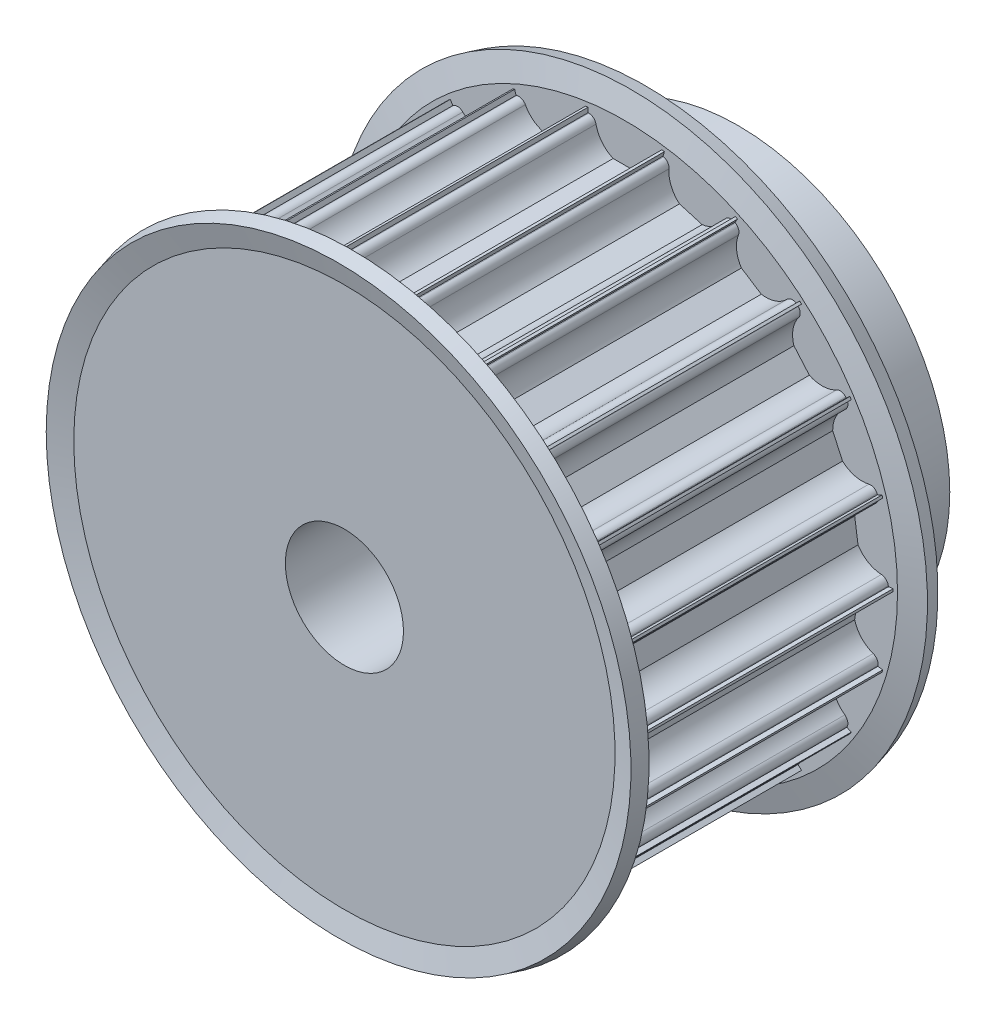
SolidWorks part; units mm, degrees
ref_plane "Front Plane" through (0, 0, 0) normal (0, 0, 1) x (1, 0, 0)
ref_plane "Top Plane" through (0, 0, 0) normal (0, 1, 0) x (1, 0, 0)
ref_plane "Right Plane" through (0, 0, 0) normal (1, 0, 0) x (0, 0, -1)
sketch "Sketch1" plane through (0, 0, 0) normal (1, 0, 0) x (0, 0, -1)
  line L0 (0, 0) -> (51.5673, 0) construction
  line L1 (0, 6) -> (40, 6)
  line L2 (40, 6) -> (40, 21.5)
  line L3 (40, 21.5) -> (30, 21.5)
  line L4 (30, 21.5) -> (30, 27.25)
  line L5 (30, 27.25) -> (0, 27.25)
  line L6 (0, 27.25) -> (0, 6)
  dimension "D1" = 27.25
  dimension "D2" = 6
  dimension "D3" = 30
  dimension "D4" = 10
  dimension "D5" = 15.5
revolve "Revolve1" add sketch "Sketch1" angle 360 about L0
sketch "Sketch2" plane through (0, 0, 0) normal (0, 0, 1) x (1, 0, 0)
  line L0 (-3.6742, 26.5) -> (-3.75, 26.5)
  line L1 (-3.75, 26.5) -> (-3.75, 28.5)
  line L2 (-3.75, 28.5) -> (3.75, 28.5)
  line L3 (3.75, 28.5) -> (3.75, 26.5)
  line L4 (3.75, 26.5) -> (3.6742, 26.5)
  line L5 (-1.199, 23.75) -> (1.199, 23.75)
  arc A0 (2.9394, 25.9) -> (1.199, 23.75) centre (0, 26.5) cw
  arc A1 (2.9394, 25.9) -> (3.6742, 26.5) centre (3.6742, 25.75) cw
  arc A2 (-2.9394, 25.9) -> (-3.6742, 26.5) centre (-3.6742, 25.75) ccw
  arc A3 (-1.199, 23.75) -> (-2.9394, 25.9) centre (0, 26.5) cw
  point P8 (0, 28.5)
  point P11 (3, 26.5)
  point P14 (-3, 26.5)
  dimension "D1" = 3
  dimension "D5" = 0.75
  dimension "D2" = 26.5
  dimension "D3" = 7.5
  dimension "D4" = 2
  dimension "D6" = 2.75
extrude "Cut-Extrude1" cut sketch "Sketch2" against normal up to next
pattern_circular "CirPattern1" count 22 over 360 about axis through (0, 0, 0) along (0, 0, 1) of "Cut-Extrude1"
sketch "Sketch3" plane through (0, 0, 0) normal (1, 0, 0) x (0, 0, -1)
  line L0 (15, 26.9539) -> (15, 10.9567) construction
  line L1 (30, 26.9539) -> (0, 26.9539) construction
  line L2 (30, 10.9567) -> (0, 10.9567) construction
  line L3 (30, 21.5) -> (30, 27.4925)
  line L4 (30, 27.4925) -> (30.592, 29.7018)
  line L5 (30.592, 29.7018) -> (29.1431, 30.09)
  line L6 (29.1431, 30.09) -> (28.5, 27.69)
  line L7 (28.5, 27.69) -> (28.5, 21.5)
  line L8 (28.5, 21.5) -> (30, 21.5)
  line L9 (0.8569, 30.09) -> (1.5, 27.69)
  line L10 (1.5, 27.69) -> (1.5, 21.5)
  line L11 (1.5, 21.5) -> (0, 21.5)
  line L12 (0, 21.5) -> (0, 27.4925)
  line L13 (0, 27.4925) -> (-0.592, 29.7018)
  line L14 (-0.592, 29.7018) -> (0.8569, 30.09)
  line L15 (0, 0) -> (-19.1733, 0) construction
  dimension "D1" = 15
  dimension "D2" = 1.5
  dimension "D3" = 6.19
  dimension "D4" = 2.4
revolve "Revolve2" add sketch "Sketch3" angle 360 about L15
